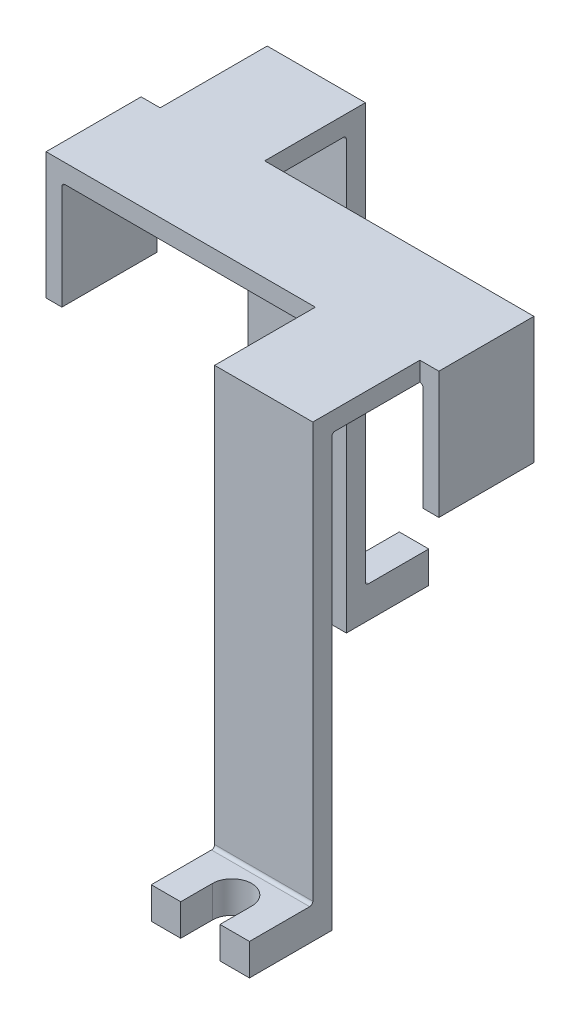
SolidWorks part; units mm, degrees
ref_plane "Alzado" through (0, 0, 0) normal (0, 0, 1) x (1, 0, 0)
ref_plane "Planta" through (0, 0, 0) normal (0, 1, 0) x (1, 0, 0)
ref_plane "Vista lateral" through (0, 0, 0) normal (1, 0, 0) x (0, 0, -1)
sketch "Croquis1" plane through (0, 0, 0) normal (0, 1, 0) x (1, 0, 0)
  line L1 (-28.1064, -8.1764) -> (11.3936, -8.1764)
  line L2 (-28.1064, -8.1764) -> (-28.1064, 6.8236)
  line L3 (-12.6064, 7.8236) -> (26.8936, 7.8236)
  line L4 (26.8936, -7.1764) -> (26.8936, 7.8236)
  line L5 (-28.1064, -8.1764) -> (26.8936, 7.8236) construction
  line L6 (-28.1064, 6.8236) -> (28.2727, -6.864) construction
  line L8 (-28.1064, 6.8236) -> (-28.1064, 23.7236)
  line L9 (-28.1064, 23.7236) -> (-12.6064, 23.7236)
  line L10 (-12.6064, 7.8236) -> (-12.6064, 23.7236)
  line L12 (26.8936, -7.1764) -> (26.8936, -24.0764)
  line L13 (26.8936, -24.0764) -> (11.3936, -24.0764)
  line L14 (11.3936, -8.1764) -> (11.3936, -24.0764)
  point P0 (0, 0)
  dimension "D1" = 55
  dimension "D2" = 47.8
  dimension "D3" = 15.5
  dimension "D4" = 15.5
  dimension "D5" = 16.9
  dimension "D6" = 16.9
  dimension "D7" = 26.8936
  dimension "D8" = 15
  dimension "D9" = 15
extrude "Saliente-Extruir1" add sketch "Croquis1" along normal blind 3
sketch "Croquis2" plane through (0, 3, 0) normal (0, 1, 0) x (1, 0, 0)
  line L0 (-28.1064, -8.1764) -> (11.3936, -8.1764) construction
  line L1 (26.8936, 7.8236) -> (29.8936, 7.8236)
  line L2 (26.8936, 7.8236) -> (26.8936, -7.1764)
  line L3 (26.8936, -7.1764) -> (29.8936, -7.1764)
  line L4 (29.8936, 7.8236) -> (29.8936, -7.1764)
  line L5 (-28.1064, -8.1764) -> (-31.1064, -8.1764)
  line L6 (-28.1064, -8.1764) -> (-28.1064, 6.8236)
  line L7 (-28.1064, 6.8236) -> (-31.1064, 6.8236)
  line L8 (-31.1064, -8.1764) -> (-31.1064, 6.8236)
  line L9 (-28.1064, -8.1764) -> (11.3936, -8.1764) construction
  line L10 (26.8936, 7.8236) -> (-12.6064, 7.8236) construction
  line L11 (26.8936, 7.8236) -> (-12.6064, 7.8236) construction
  dimension "D1" = 3
  dimension "D2" = 3
  dimension "D3" = 15
  dimension "D4" = 15
extrude "Saliente-Extruir2" add sketch "Croquis2" against normal blind 3
sketch "Croquis3" plane through (0, 0, 0) normal (0, -1, 0) x (1, 0, 0)
  line L0 (-28.1064, -6.8236) -> (-31.1064, -6.8236) construction
  line L1 (-31.1064, 8.1764) -> (-28.6064, 8.1764)
  line L2 (-31.1064, 8.1764) -> (-31.1064, -6.8236)
  line L3 (-31.1064, -6.8236) -> (-28.6064, -6.8236)
  line L4 (-28.6064, 8.1764) -> (-28.6064, -6.8236)
  line L5 (29.8936, -7.8236) -> (-12.6064, -7.8236) construction
  line L6 (29.8936, 7.1764) -> (27.3936, 7.1764)
  line L7 (29.8936, 7.1764) -> (29.8936, -7.8236)
  line L8 (29.8936, -7.8236) -> (27.3936, -7.8236)
  line L9 (27.3936, 7.1764) -> (27.3936, -7.8236)
  dimension "D1" = 2.5
  dimension "D2" = 2.5
extrude "Saliente-Extruir3" add sketch "Croquis3" along normal blind 17
sketch "Croquis4" plane through (0, 0, 0) normal (0, -1, 0) x (1, 0, 0)
  line L0 (-28.1064, -23.7236) -> (-28.1064, -6.8236) construction
  line L1 (-12.6064, -23.7236) -> (-28.1064, -23.7236)
  line L2 (-12.6064, -23.7236) -> (-12.6064, -20.7236)
  line L3 (-12.6064, -20.7236) -> (-28.1064, -20.7236)
  line L4 (-28.1064, -23.7236) -> (-28.1064, -20.7236)
  line L5 (26.8936, 24.0764) -> (26.8936, 7.1764) construction
  line L6 (11.3936, 24.0764) -> (26.8936, 24.0764)
  line L7 (11.3936, 24.0764) -> (11.3936, 21.0764)
  line L8 (11.3936, 21.0764) -> (26.8936, 21.0764)
  line L9 (26.8936, 24.0764) -> (26.8936, 21.0764)
  dimension "D1" = 3
  dimension "D2" = 3
extrude "Saliente-Extruir4" add sketch "Croquis4" along normal blind 68
sketch "Croquis5" plane through (0, 0, -23.7236) normal (0, 0, -1) x (-1, 0, 0)
  line L0 (28.1064, 3) -> (28.1064, -68) construction
  line L1 (12.6064, -68) -> (28.1064, -68)
  line L2 (12.6064, -68) -> (12.6064, -63)
  line L3 (12.6064, -63) -> (28.1064, -63)
  line L4 (28.1064, -68) -> (28.1064, -63)
  dimension "D1" = 5
extrude "Saliente-Extruir5" add sketch "Croquis5" along normal blind 10
sketch "Croquis6" plane through (0, 0, 24.0764) normal (0, 0, 1) x (1, 0, 0)
  line L0 (26.8936, 3) -> (26.8936, -68) construction
  line L1 (11.3936, -68) -> (26.8936, -68)
  line L2 (11.3936, -68) -> (11.3936, -63)
  line L3 (11.3936, -63) -> (26.8936, -63)
  line L4 (26.8936, -68) -> (26.8936, -63)
  dimension "D1" = 5
extrude "Saliente-Extruir6" add sketch "Croquis6" along normal blind 10
sketch "Croquis7" plane through (0, -63, 0) normal (0, 1, 0) x (1, 0, 0)
  line L0 (19.1436, -34.0764) -> (19.1436, -29.0764) construction
  line L1 (26.8936, -34.0764) -> (11.3936, -34.0764) construction
  line L2 (16.0436, -29.0764) -> (16.0436, -34.0764)
  line L3 (16.0436, -34.0764) -> (22.2436, -34.0764)
  line L4 (22.2436, -34.0764) -> (22.2436, -29.0764)
  arc A0 (22.2436, -29.0764) -> (16.0436, -29.0764) centre (19.1436, -29.0764) ccw
  dimension "D2" = 6.2
  dimension "D1" = 5
extrude "Cortar-Extruir1" cut sketch "Croquis7" against normal blind 10
sketch "Croquis8" plane through (0, -63, 0) normal (0, 1, 0) x (1, 0, 0)
  line L0 (-20.3564, 33.7236) -> (-20.3564, 28.7236) construction
  line L1 (-28.1064, 33.7236) -> (-12.6064, 33.7236) construction
  line L2 (-23.4564, 28.7236) -> (-23.4564, 33.7236)
  line L3 (-23.4564, 33.7236) -> (-17.2564, 33.7236)
  line L4 (-17.2564, 33.7236) -> (-17.2564, 28.7236)
  arc A0 (-23.4564, 28.7236) -> (-17.2564, 28.7236) centre (-20.3564, 28.7236) ccw
  dimension "D2" = 6.2
  dimension "D1" = 5
extrude "Cortar-Extruir2" cut sketch "Croquis8" against normal blind 10
fillet "Redondeo2" radius 0.5 6 edges at (19.1436, -63, 24.0764) (19.1436, 0, 21.0764) (27.3936, 0, -0.3236) (-28.6064, 0, 0.6764) (-20.3564, 0, -20.7236) (-20.3564, -63, -23.7236)
